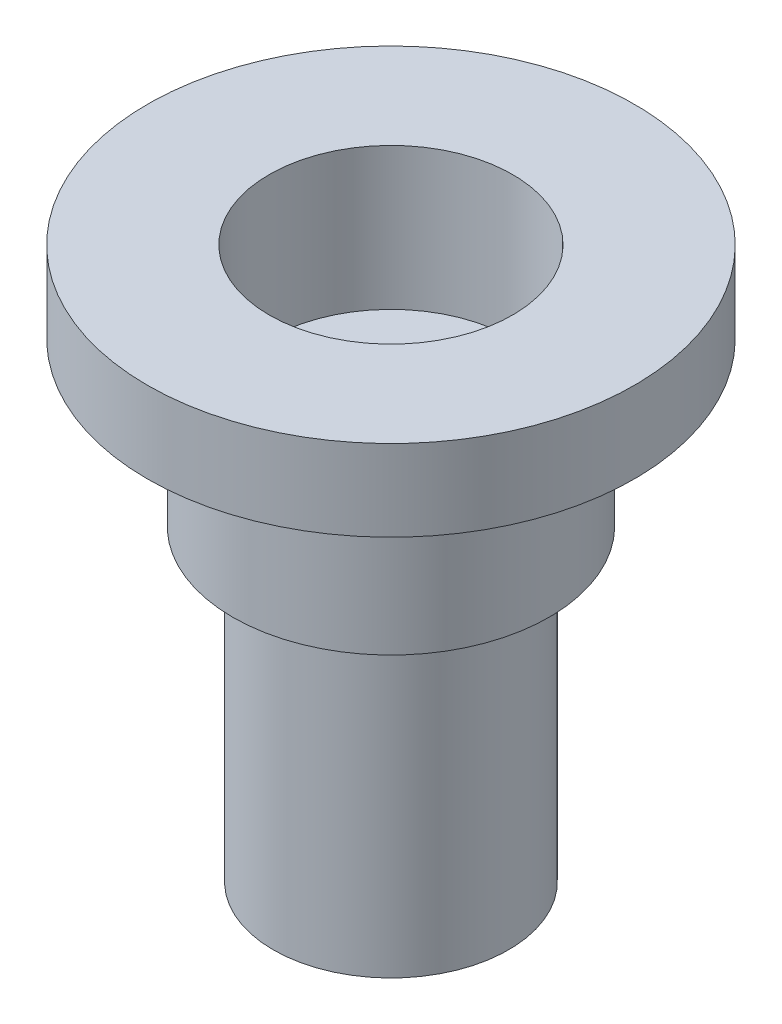
SolidWorks part; units mm, degrees
ref_plane "Front Plane" through (0, 0, 0) normal (0, 0, 1) x (1, 0, 0)
ref_plane "Top Plane" through (0, 0, 0) normal (0, 1, 0) x (1, 0, 0)
ref_plane "Right Plane" through (0, 0, 0) normal (1, 0, 0) x (0, 0, -1)
sketch "草图1" plane through (0, 0, 0) normal (0, 1, 0) x (1, 0, 0)
  circle A0 centre (0, 0) radius 3.9
  dimension "D1" = 7.8
extrude "凸台-拉伸1" add sketch "草图1" along normal blind 4
sketch "草图2" plane through (0, 4, 0) normal (0, 1, 0) x (1, 0, 0)
  circle A0 centre (0, 0) radius 6
  dimension "D1" = 12
extrude "凸台-拉伸2" add sketch "草图2" along normal blind 2
sketch "草图3" plane through (0, 6, 0) normal (0, 1, 0) x (1, 0, 0)
  circle A0 centre (0, 0) radius 1.6
  dimension "D1" = 3.2
sketch "草图4" plane through (0, 6, 0) normal (0, 1, 0) x (1, 0, 0)
  circle A0 centre (0, 0) radius 3
  dimension "D1" = 6
sketch "草图6" plane through (0, 0, 0) normal (0, -1, 0) x (1, 0, 0)
  circle A0 centre (0, 0) radius 2.9
  dimension "D1" = 5.8
extrude "凸台-拉伸3" add sketch "草图6" along normal blind 7.6
extrude "切除-拉伸1" cut sketch "草图3" against normal through all contours A0
extrude "切除-拉伸2" cut sketch "草图4" against normal blind 3.5
